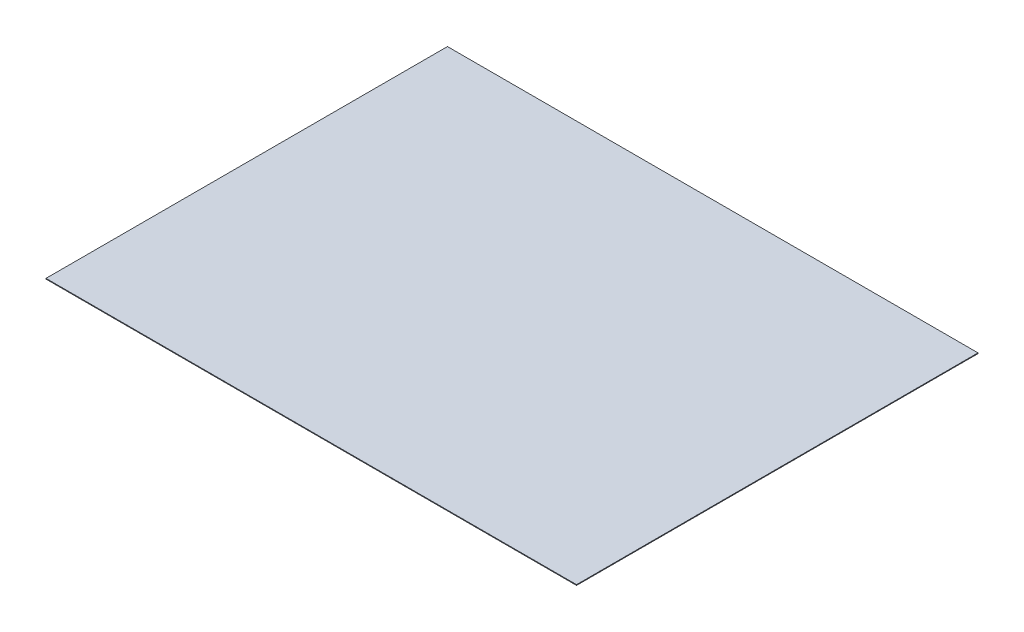
SolidWorks part; units mm, degrees
ref_plane "Alzado" through (0, 0, 0) normal (0, 0, 1) x (1, 0, 0)
ref_plane "Planta" through (0, 0, 0) normal (0, 1, 0) x (1, 0, 0)
ref_plane "Vista lateral" through (0, 0, 0) normal (1, 0, 0) x (0, 0, -1)
sketch "Croquis1" plane through (0, 0, 0) normal (0, 1, 0) x (1, 0, 0)
  line L1 (766.5, -580) -> (-766.5, -580)
  line L2 (766.5, -580) -> (766.5, 580)
  line L3 (766.5, 580) -> (-766.5, 580)
  line L4 (-766.5, -580) -> (-766.5, 580)
  line L5 (766.5, -580) -> (-766.5, 580) construction
  line L6 (766.5, 580) -> (-766.5, -580) construction
  point P0 (0, 0)
  dimension "D1" = 1533
  dimension "D2" = 1160
extrude "Extruir1" add sketch "Croquis1" along normal blind 2
